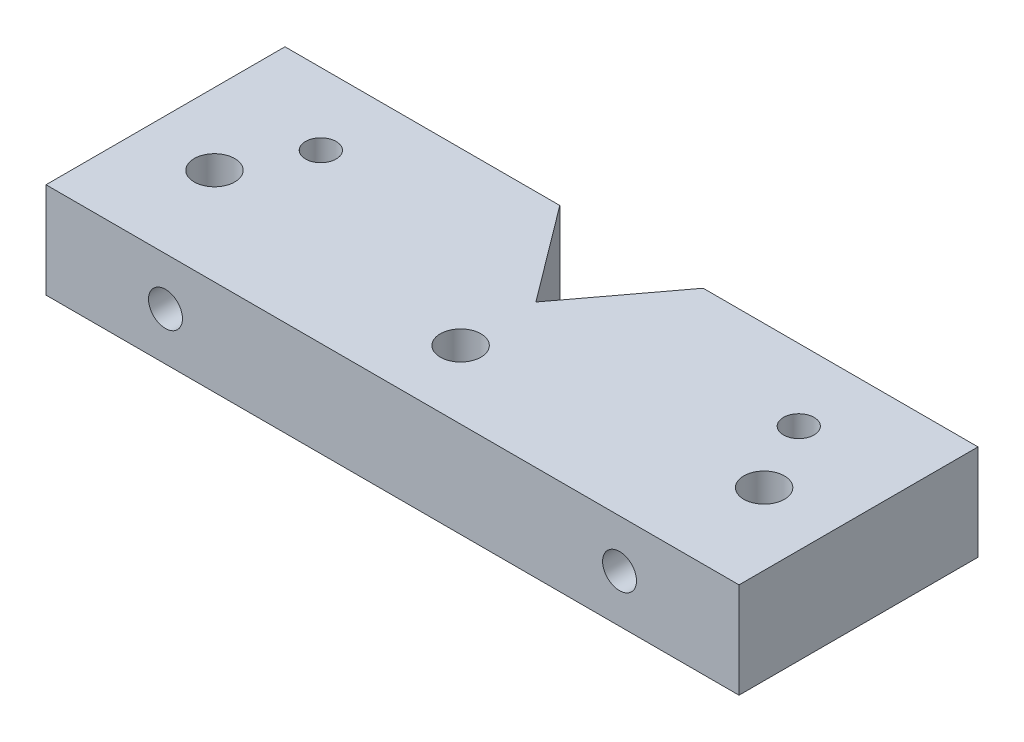
SolidWorks part; units mm, degrees
ref_plane "Front Plane" through (0, 0, 0) normal (0, 0, 1) x (1, 0, 0)
ref_plane "Top Plane" through (0, 0, 0) normal (0, 1, 0) x (1, 0, 0)
ref_plane "Right Plane" through (0, 0, 0) normal (1, 0, 0) x (0, 0, -1)
sketch "Sketch1" plane through (0, 0, 0) normal (0, 1, 0) x (1, 0, 0)
  line L0 (0, 0) -> (0, 50)
  line L1 (0, 50) -> (57.5, 50)
  line L2 (57.5, 50) -> (72.5, 30)
  line L3 (72.5, 30) -> (87.5, 50)
  line L4 (87.5, 50) -> (145, 50)
  line L5 (145, 50) -> (145, 0)
  line L6 (145, 0) -> (0, 0)
  line L7 (0, 20.25) -> (145, 20.25) construction
  line L8 (0, 14.25) -> (145, 14.25) construction
  line L9 (72.5, 30) -> (72.5, 0) construction
  circle A1 centre (15, 20.25) radius 4.25
  circle A2 centre (72.5, 14.25) radius 4.25
  circle A3 centre (130, 20.25) radius 4.25
  dimension "D5" = 8.5
  dimension "D6" = 8.5
  dimension "D7" = 8.5
  dimension "D1" = 50
  dimension "D2" = 20
  dimension "D3" = 145
  dimension "D4" = 30
  dimension "D8" = 14.25
  dimension "D9" = 20.25
  dimension "D10" = 57.5
  dimension "D11" = 57.5
extrude "Boss-Extrude1" add sketch "Sketch1" along normal blind 20
sketch "Sketch2" plane through (0, 20, 0) normal (0, 1, 0) x (1, 0, 0)
  line L0 (0, 35) -> (145, 35) construction
  line L1 (0, 50) -> (0, 0) construction
  line L2 (145, 0) -> (145, 50) construction
  line L3 (0, 0) -> (145, 0) construction
  line L4 (72.5, 30) -> (72.5, 0) construction
  circle A0 centre (22.5, 35) radius 3.2
  circle A1 centre (122.5, 35) radius 3.2
  dimension "D2" = 6.4
  dimension "D3" = 6.4
  dimension "D1" = 35
  dimension "D4" = 50
  dimension "D5" = 50
sketch "Sketch3" plane through (0, 0, 0) normal (0, 0, 1) x (1, 0, 0)
  line L0 (0, 10) -> (145, 10) construction
  line L1 (0, 20) -> (0, 0) construction
  line L2 (145, 20) -> (145, 0) construction
  circle A0 centre (25, 10) radius 3.55
  circle A1 centre (120, 10) radius 3.55
  dimension "D3" = 7.1
  dimension "D4" = 7.1
  dimension "D1" = 25
  dimension "D2" = 25
extrude "Cut-Extrude2" cut sketch "Sketch3" against normal blind 10.5
extrude "Cut-Extrude3" cut sketch "Sketch2" against normal blind 10.5
equation "\"SyringeDiameter\"= 20"
equation "\"SyringeLength\"= 100"
equation "\"PlungerDiameter\"= 5"
equation "\"PlungerLength\"= 110"
equation "\"VSlotWidth\"= 30"
equation "\"VSlotDepth\"= 20"
equation "\"FingerFlangeDiameter\"= 30"
equation "\"VSlotBackPlateThickness\"= 5"
equation "\"GuideRodDiameter\"= 8.5"
equation "\"LeadScrewDiameter\"= 8.5"
equation "\"GuideRodSpacing\" = 16.25 + 4"
equation "\"LeadScrewSpacing\" = 10.25 + 4"
equation "\"ThreadedInsertDiameter\"= 7.1"
equation "\"ThreadedInsertDepth\"= 10.5"
equation "\"MountingHoleDiameter\"= 3"
equation "\"MountingHoleSpacing\"= 20"
equation "\"BlockHeight\" = 50"
equation "\"BlockWidth\"= \"RodToScrew\" * 2 + 30"
equation "\"BlockDepth\"= 20"
equation "\"VSlotAngle\"= 90"
equation "\"D1@Sketch1\"=\"BlockHeight\""
equation "\"D2@Sketch1\"=\"VSlotDepth\""
equation "\"D3@Sketch1\"=\"BlockWidth\""
equation "\"D4@Sketch1\"=\"VSlotWidth\""
equation "\"D5@Sketch1\"=\"GuideRodDiameter\""
equation "\"D6@Sketch1\"=\"GuideRodDiameter\""
equation "\"D7@Sketch1\"=\"LeadScrewDiameter\""
equation "\"D8@Sketch1\"=\"LeadScrewSpacing\""
equation "\"D9@Sketch1\"=\"GuideRodSpacing\""
equation "\"GuideRodSideWidth\"= 10"
equation "\"D1@Boss-Extrude1\"=\"VSlotDepth\""
equation "\"ScrewHeight\" = 35"
equation "\"D1@Sketch2\"=\"ScrewHeight\""
equation "\"ThreadedInsertSideWidth\" = 50"
equation "\"D1@Cut-Extrude1\"=\"ThreadedInsertDepth\""
equation "\"ScrewMountDistance\"= 25"
equation "\"D1@Sketch3\"=\"ScrewMountDistance\""
equation "\"D2@Sketch3\"=\"ScrewMountDistance\""
equation "\"D3@Sketch3\"=\"ThreadedInsertDiameter\""
equation "\"D4@Sketch3\"=\"ThreadedInsertDiameter\""
equation "\"D1@Cut-Extrude2\"=\"ThreadedInsertDepth\""
equation "\"RodtoRod\"= 115"
equation "\"RodToScrew\"= \"RodtoRod\" / 2"
equation "\"D10@Sketch1\"=\"RodToScrew\""
equation "\"D4@Sketch2\"=\"ThreadedInsertSideWidth\""
equation "\"D5@Sketch2\"=\"ThreadedInsertSideWidth\""
